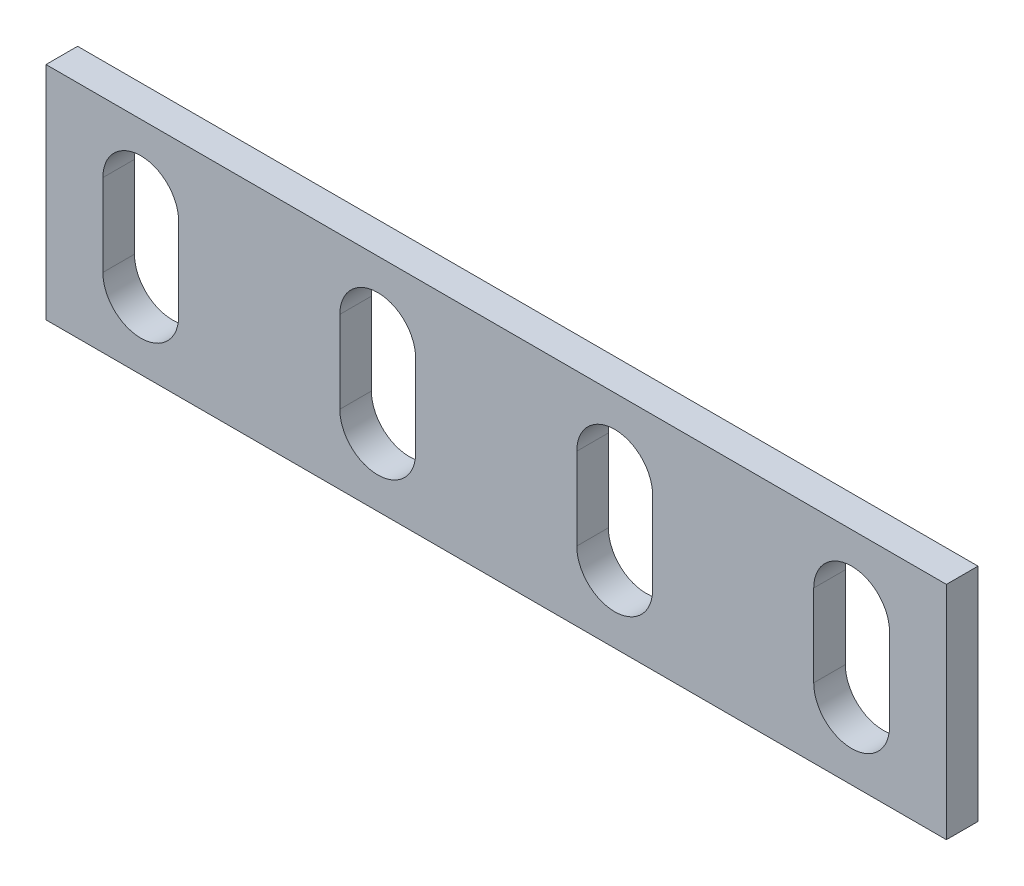
SolidWorks part; units mm, degrees
ref_plane "Front Plane" through (0, 0, 0) normal (0, 0, 1) x (1, 0, 0)
ref_plane "Top Plane" through (0, 0, 0) normal (0, 1, 0) x (1, 0, 0)
ref_plane "Right Plane" through (0, 0, 0) normal (1, 0, 0) x (0, 0, -1)
sketch "Sketch1" plane through (0, 0, 0) normal (0, 0, 1) x (1, 0, 0)
  line L0 (0, 230.3765) -> (0, -159.1465) construction
  line L1 (-285, 70) -> (285, 70)
  line L2 (-285, 70) -> (-285, -70)
  line L3 (-285, -70) -> (285, -70)
  line L4 (285, 70) -> (285, -70)
  line L5 (-350.8734, 0) -> (603.7909, 0) construction
  line L6 (75, 26) -> (75, -26) construction
  line L9 (99, 26) -> (99, -26)
  line L10 (51, 26) -> (51, -26)
  line L11 (225, 26) -> (225, -26) construction
  line L12 (249, 26) -> (249, -26)
  line L13 (201, 26) -> (201, -26)
  line L14 (-75, 26) -> (-75, -26) construction
  line L15 (-99, 26) -> (-99, -26)
  line L16 (-51, 26) -> (-51, -26)
  line L17 (-225, 26) -> (-225, -26) construction
  line L18 (-249, 26) -> (-249, -26)
  line L19 (-201, 26) -> (-201, -26)
  arc A2 (99, 26) -> (51, 26) centre (75, 26) ccw
  arc A3 (51, -26) -> (99, -26) centre (75, -26) ccw
  arc A4 (249, 26) -> (201, 26) centre (225, 26) ccw
  arc A5 (201, -26) -> (249, -26) centre (225, -26) ccw
  arc A6 (-99, 26) -> (-51, 26) centre (-75, 26) cw
  arc A7 (-51, -26) -> (-99, -26) centre (-75, -26) cw
  arc A8 (-249, 26) -> (-201, 26) centre (-225, 26) cw
  arc A9 (-201, -26) -> (-249, -26) centre (-225, -26) cw
  point P11 (75, 0)
  point P20 (225, 0)
  point P25 (-75, 0)
  point P32 (-225, 0)
  dimension "D7" = 52
  dimension "D8" = 48
  dimension "D6" = 24
  dimension "D1" = 570
  dimension "D2" = 140
  dimension "D3" = 285
  dimension "D4" = 70
  dimension "D5" = 75
  dimension "D9" = 2
extrude "Boss-Extrude1" add sketch "Sketch1" along normal blind 20
